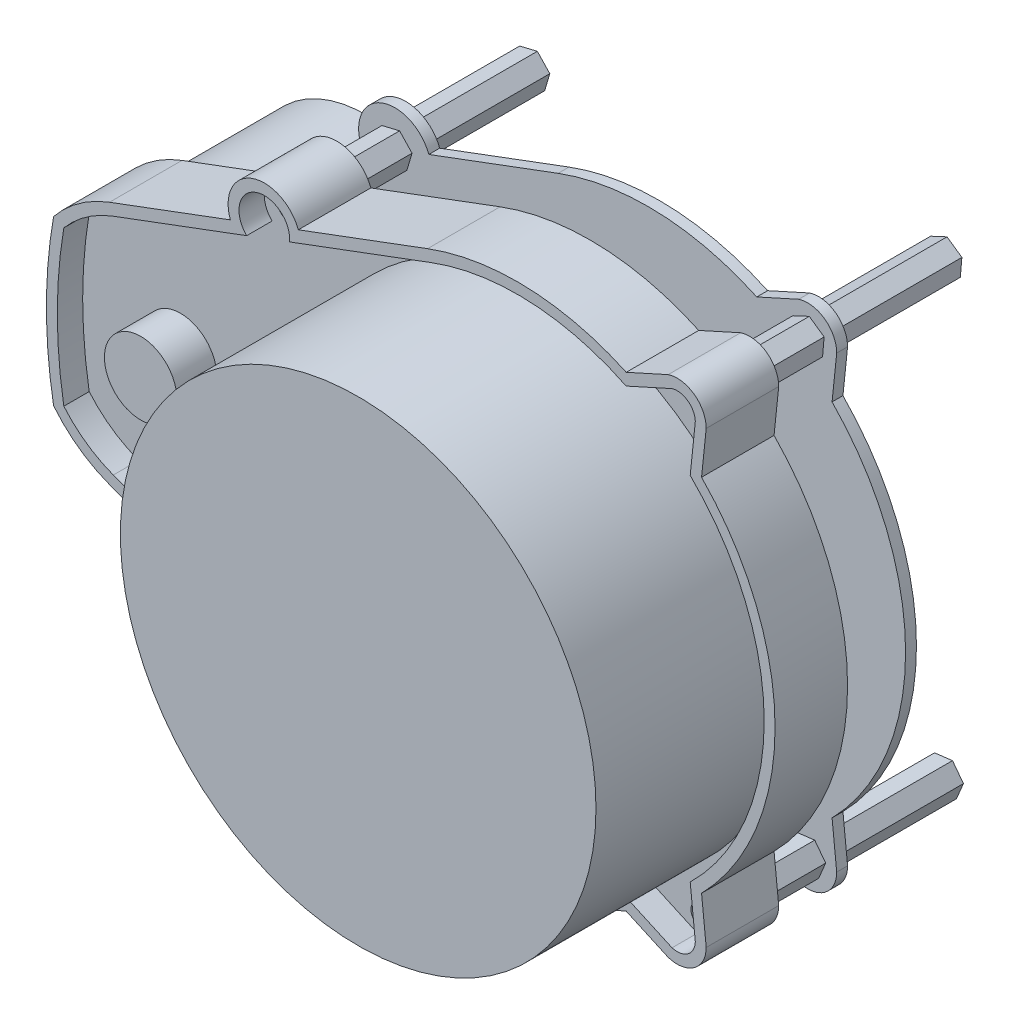
SolidWorks part; units mm, degrees
ref_plane "Plan de face" through (0, 0, 0) normal (0, 0, 1) x (1, 0, 0)
ref_plane "Plan de dessus" through (0, 0, 0) normal (0, 1, 0) x (1, 0, 0)
ref_plane "Plan de droite" through (0, 0, 0) normal (1, 0, 0) x (0, 0, -1)
sketch "Esquisse1" plane through (0, 0, 0) normal (0, 0, 1) x (1, 0, 0)
  line L0 (-12.425, 33.2546) -> (-30.2572, 26.5919)
  line L1 (-56.3, 16.8615) -> (-56.3, -16.8615) construction
  line L2 (-50, 0) -> (0, 0) construction
  line L3 (-12.425, 33.2546) -> (-12.425, -33.2546) construction
  line L5 (-35, 25) -> (-34.9409, 24.8419) construction
  line L6 (-39.6247, 23.0919) -> (-56.3, 16.8615)
  line L7 (-33.4505, 25.3988) -> (-36.4314, 24.2851)
  line L8 (20.756, 34.8016) -> (14.974, 32.1874)
  line L9 (26, 31) -> (25.36, 24.8419)
  line L10 (-65, 0) -> (35.5, 0) construction
  line L11 (55, 0) -> (-55, 0) construction
  line L12 (-35, -25) -> (-34.9409, -24.8419) construction
  line L13 (26, -31) -> (25.36, -24.8419)
  line L14 (20.756, -34.8016) -> (14.974, -32.1874)
  line L15 (-33.4505, -25.3988) -> (-36.4314, -24.2851)
  line L16 (-39.6247, -23.0919) -> (-56.3, -16.8615)
  line L17 (-12.425, -33.2546) -> (-30.2572, -26.5919)
  arc A1 (25.36, -24.8419) -> (25.36, 24.8419) centre (0, 0) ccw
  arc A3 (-64.01, 11.3013) -> (-64.01, -11.3013) centre (0, 0) ccw
  arc A4 (-56.3, 16.8615) -> (-64.01, 11.3013) centre (-50, 0) ccw
  circle A5 centre (22, 31) radius 1.6
  circle A6 centre (-35, 25) radius 1.6
  arc A7 (-30.2572, 26.5919) -> (-39.6247, 23.0919) centre (-34.9409, 24.8419) ccw
  arc A8 (26, 31) -> (20.756, 34.8016) centre (22, 31) ccw
  arc A9 (14.974, 32.1874) -> (-12.425, 33.2546) centre (0, 0) ccw
  arc A10 (14.974, -32.1874) -> (-12.425, -33.2546) centre (0, 0) cw
  arc A11 (26, -31) -> (20.756, -34.8016) centre (22, -31) cw
  arc A12 (-30.2572, -26.5919) -> (-39.6247, -23.0919) centre (-34.9409, -24.8419) cw
  circle A13 centre (-35, -25) radius 1.6
  circle A14 centre (22, -31) radius 1.6
  arc A15 (-56.3, -16.8615) -> (-64.01, -11.3013) centre (-50, 0) cw
  point P28 (-12.425, 0)
  point P29 (-56.3, 0)
  dimension "D1" = 71
  dimension "D4" = 130
  dimension "D6" = 3.2
  dimension "D10" = 10
  dimension "D11" = 8
  dimension "D3" = 50
  dimension "D5" = 31
  dimension "D7" = 22
  dimension "D8" = 35
  dimension "D9" = 25
extrude "Boss.-Extru.1" add sketch "Esquisse1" along normal blind 10 contours A15 L16 A12 L17 A10 L14 A11 L13 A1 L9 A8 L8 A9 L0 A7 L6 A4 A3 A13 A5 A6 A14
sketch "Esquisse2" plane through (0, 0, 10) normal (0, 0, 1) x (1, 0, 0)
  circle A0 centre (0, 0) radius 32.8
  dimension "D1" = 65.6
extrude "Boss.-Extru.2" add sketch "Esquisse2" along normal blind 22
sketch "Esquisse3" plane through (0, 0, 10) normal (0, 0, 1) x (1, 0, 0)
  line L16 (-55.775, -15.4564) -> (-37.3782, -22.33)
  line L17 (14.9568, -30.5335) -> (21.2911, -33.3974)
  line L18 (24.4991, -31.0687) -> (23.7942, -24.2866)
  line L19 (23.7942, 24.2866) -> (24.4991, 31.0687)
  line L20 (21.2911, 33.3974) -> (14.9568, 30.5335)
  line L21 (-11.9, 31.8495) -> (-31.4537, 24.5436)
  line L22 (-55.775, -15.4564) -> (-37.3782, -22.33)
  line L23 (14.9568, -30.5335) -> (21.2911, -33.3974)
  line L24 (24.4991, -31.0687) -> (23.7942, -24.2866)
  line L25 (23.7942, 24.2866) -> (24.4991, 31.0687)
  line L26 (21.2911, 33.3974) -> (14.9568, 30.5335)
  line L27 (-11.9, 31.8495) -> (-31.4537, 24.5436)
  line L28 (-31.4537, -24.5436) -> (-11.9, -31.8495)
  line L29 (-31.4537, -24.5436) -> (-11.9, -31.8495)
  line L30 (-37.3782, 22.33) -> (-55.775, 15.4564)
  line L31 (-37.3782, 22.33) -> (-55.775, 15.4564)
  arc A20 (-62.6, -10.6532) -> (-55.775, -15.4564) centre (-50, 0) ccw
  arc A21 (-11.9, -31.8495) -> (14.9568, -30.5335) centre (0, 0) ccw
  arc A22 (23.7942, -24.2866) -> (23.7942, 24.2866) centre (0, 0) ccw
  arc A23 (14.9568, 30.5335) -> (-11.9, 31.8495) centre (0, 0) ccw
  arc A24 (-55.775, 15.4564) -> (-62.6, 10.6532) centre (-50, 0) ccw
  arc A25 (-62.6, 10.6532) -> (-62.6, -10.6532) centre (0, 0) ccw
  arc A26 (-62.6, -10.6532) -> (-55.775, -15.4564) centre (-50, 0) ccw
  arc A27 (-11.9, -31.8495) -> (14.9568, -30.5335) centre (0, 0) ccw
  arc A28 (23.7942, -24.2866) -> (23.7942, 24.2866) centre (0, 0) ccw
  arc A29 (14.9568, 30.5335) -> (-11.9, 31.8495) centre (0, 0) ccw
  arc A30 (-55.775, 15.4564) -> (-62.6, 10.6532) centre (-50, 0) ccw
  arc A31 (-62.6, 10.6532) -> (-62.6, -10.6532) centre (0, 0) ccw
  arc A32 (-37.3782, -22.33) -> (-31.4537, -24.5436) centre (-34.9409, -24.8419) ccw
  arc A33 (-37.3782, -22.33) -> (-31.4537, -24.5436) centre (-34.9409, -24.8419) ccw
  arc A34 (21.2911, -33.3974) -> (24.4991, -31.0687) centre (22, -31) ccw
  arc A35 (21.2911, -33.3974) -> (24.4991, -31.0687) centre (22, -31) ccw
  arc A36 (24.4991, 31.0687) -> (21.2911, 33.3974) centre (22, 31) ccw
  arc A37 (24.4991, 31.0687) -> (21.2911, 33.3974) centre (22, 31) ccw
  arc A38 (-31.4537, 24.5436) -> (-37.3782, 22.33) centre (-34.9409, 24.8419) ccw
  arc A39 (-31.4537, 24.5436) -> (-37.3782, 22.33) centre (-34.9409, 24.8419) ccw
  dimension "D1" = 1.5
extrude "Enlèv. mat.-Extru.1" cut sketch "Esquisse3" against normal blind 3.5
sketch "Esquisse4" plane through (0, 0, 10) normal (0, 0, -1) x (-1, 0, 0)
  circle A1 centre (0, 0) radius 32.8
  circle A2 centre (0, 0) radius 32.8
  dimension "D1" = 0
extrude "Boss.-Extru.3" add sketch "Esquisse4" along normal up to next
sketch "Esquisse5" plane through (0, 0, 0) normal (0, 0, -1) x (-1, 0, 0)
  circle A0 centre (50, 0) radius 16
  dimension "D2" = 32
  dimension "D1" = 50
extrude "Boss.-Extru.4" add sketch "Esquisse5" along normal blind 19
sketch "Esquisse6" plane through (0, 0, 0) normal (0, 0, -1) x (-1, 0, 0)
  line L1 (-20.4892, -29.0081) -> (-22.9696, -28.6957)
  line L2 (-22.9696, -28.6957) -> (-24.4804, -30.6876)
  line L3 (-24.4804, -30.6876) -> (-23.5108, -32.9919)
  line L4 (-23.5108, -32.9919) -> (-21.0304, -33.3043)
  line L5 (-21.0304, -33.3043) -> (-19.5196, -31.3124)
  line L6 (-19.5196, -31.3124) -> (-20.4892, -29.0081)
  line L7 (36.0868, -22.7486) -> (33.5937, -22.9331)
  line L8 (33.5937, -22.9331) -> (32.5068, -25.1845)
  line L9 (32.5068, -25.1845) -> (33.9132, -27.2514)
  line L10 (33.9132, -27.2514) -> (36.4063, -27.0669)
  line L11 (36.4063, -27.0669) -> (37.4932, -24.8155)
  line L12 (37.4932, -24.8155) -> (36.0868, -22.7486)
  line L13 (36.7203, 26.814) -> (34.2892, 27.3968)
  line L14 (34.2892, 27.3968) -> (32.5689, 25.5828)
  line L15 (32.5689, 25.5828) -> (33.2797, 23.186)
  line L16 (33.2797, 23.186) -> (35.7108, 22.6032)
  line L17 (35.7108, 22.6032) -> (37.4311, 24.4172)
  line L18 (37.4311, 24.4172) -> (36.7203, 26.814)
  line L19 (-19.9522, 32.434) -> (-22.218, 33.4905)
  line L20 (-22.218, 33.4905) -> (-24.2658, 32.0565)
  line L21 (-24.2658, 32.0565) -> (-24.0478, 29.566)
  line L22 (-24.0478, 29.566) -> (-21.782, 28.5095)
  line L23 (-21.782, 28.5095) -> (-19.7342, 29.9435)
  line L24 (-19.7342, 29.9435) -> (-19.9522, 32.434)
  circle A0 centre (-22, -31) radius 2.1651 construction
  circle A1 centre (35, -25) radius 2.1651 construction
  circle A2 centre (35, 25) radius 2.1651 construction
  circle A3 centre (-22, 31) radius 2.1651 construction
  circle A4 centre (35, -25) radius 1
  circle A5 centre (35, 25) radius 1
  circle A6 centre (-22, 31) radius 1
  circle A7 centre (-22, -31) radius 1
  dimension "D2" = 2
  dimension "D1" = 5
extrude "Boss.-Extru.5" add sketch "Esquisse6" along normal blind 27
ref_plane "Plan1" through (0, 0, -8) normal (0, 0, -1) x (-1, 0, 0)
sketch "Esquisse7" plane through (0, 0, -8) normal (0, 0, -1) x (-1, 0, 0)
  line L0 (50, 0) -> (80, 0) construction
  line L8 (56.3, 16.8615) -> (39.6247, 23.0919)
  line L9 (30.2572, 26.5919) -> (12.425, 33.2546)
  line L10 (-14.974, 32.1874) -> (-20.756, 34.8016)
  line L11 (-26, 31) -> (-25.36, 24.8419)
  line L12 (-25.36, -24.8419) -> (-26, -31)
  line L13 (-20.756, -34.8016) -> (-14.974, -32.1874)
  line L14 (12.425, -33.2546) -> (30.2572, -26.5919)
  line L15 (39.6247, -23.0919) -> (56.3, -16.8615)
  line L17 (30.2572, 26.5919) -> (12.425, 33.2546)
  line L18 (-14.974, 32.1874) -> (-20.756, 34.8016)
  line L19 (-26, 31) -> (-25.36, 24.8419)
  line L20 (-25.36, -24.8419) -> (-26, -31)
  line L21 (-20.756, -34.8016) -> (-14.974, -32.1874)
  line L22 (12.425, -33.2546) -> (30.2572, -26.5919)
  arc A0 (39.6247, 23.0919) -> (39.6247, -23.0919) centre (80, 0) ccw
  arc A12 (64.69, 6.3407) -> (64.69, -6.3407) centre (50, 0) ccw
  arc A13 (64.69, 6.3407) -> (64.01, 11.3013) centre (0, 0) ccw
  arc A14 (64.01, 11.3013) -> (56.3, 16.8615) centre (50, 0) ccw
  arc A15 (39.6247, 23.0919) -> (30.2572, 26.5919) centre (34.9409, 24.8419) ccw
  arc A16 (12.425, 33.2546) -> (-14.974, 32.1874) centre (0, 0) ccw
  arc A17 (-20.756, 34.8016) -> (-26, 31) centre (-22, 31) ccw
  arc A18 (-25.36, 24.8419) -> (-25.36, -24.8419) centre (0, 0) ccw
  arc A19 (-26, -31) -> (-20.756, -34.8016) centre (-22, -31) ccw
  arc A20 (-14.974, -32.1874) -> (12.425, -33.2546) centre (0, 0) ccw
  arc A21 (30.2572, -26.5919) -> (39.6247, -23.0919) centre (34.9409, -24.8419) ccw
  arc A22 (56.3, -16.8615) -> (64.01, -11.3013) centre (50, 0) ccw
  arc A23 (64.01, -11.3013) -> (64.69, -6.3407) centre (0, 0) ccw
  arc A27 (39.6247, 23.0919) -> (30.2572, 26.5919) centre (34.9409, 24.8419) ccw
  arc A28 (12.425, 33.2546) -> (-14.974, 32.1874) centre (0, 0) ccw
  arc A29 (-20.756, 34.8016) -> (-26, 31) centre (-22, 31) ccw
  arc A30 (-25.36, 24.8419) -> (-25.36, -24.8419) centre (0, 0) ccw
  arc A31 (-26, -31) -> (-20.756, -34.8016) centre (-22, -31) ccw
  arc A32 (-14.974, -32.1874) -> (12.425, -33.2546) centre (0, 0) ccw
  arc A33 (30.2572, -26.5919) -> (39.6247, -23.0919) centre (34.9409, -24.8419) ccw
  point P0 (0, 0)
  dimension "D2" = 30
  dimension "D1" = 0
extrude "Boss.-Extru.6" add sketch "Esquisse7" along normal blind 1.5
sketch "Esquisse8" plane through (0, 0, 6.5) normal (0, 0, 1) x (1, 0, 0)
  circle A0 centre (-50, 0) radius 5
  dimension "D1" = 10
extrude "Boss.-Extru.7" add sketch "Esquisse8" along normal blind 5.5
